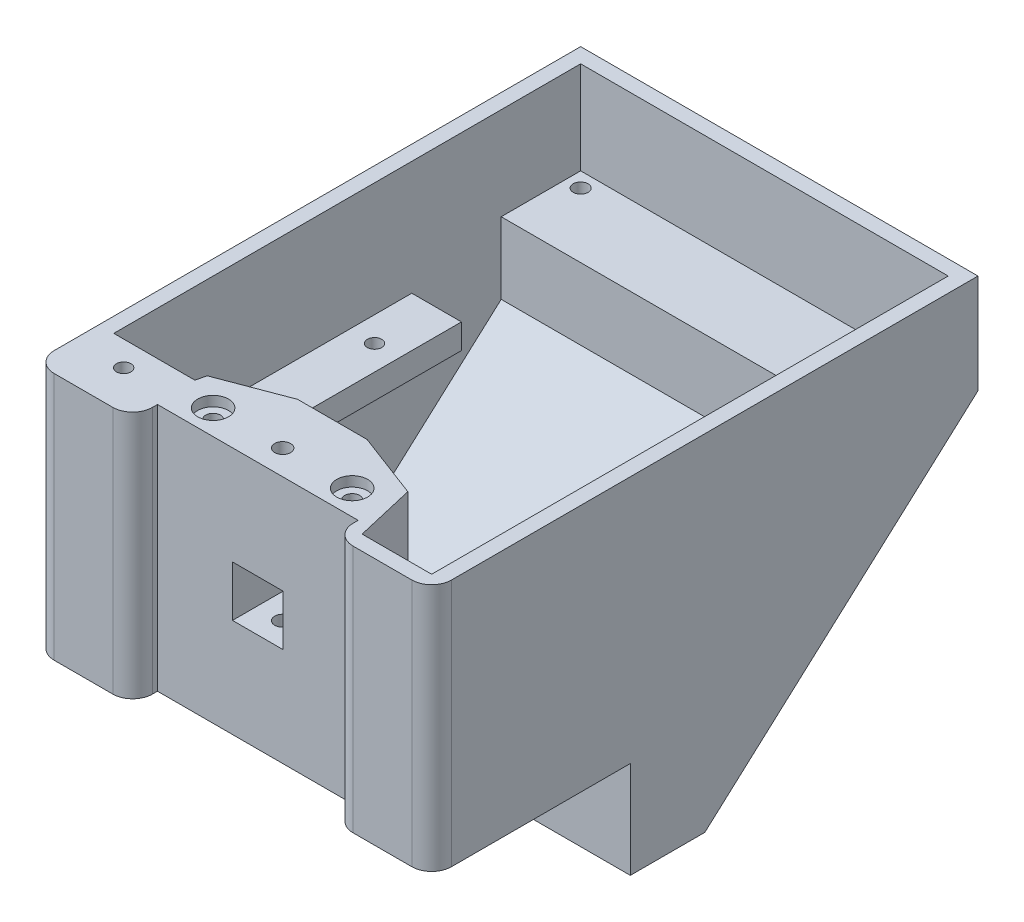
SolidWorks part; units mm, degrees
ref_plane "Спереди" through (0, 0, 0) normal (0, 0, 1) x (1, 0, 0)
ref_plane "Сверху" through (0, 0, 0) normal (0, 1, 0) x (1, 0, 0)
ref_plane "Справа" through (0, 0, 0) normal (1, 0, 0) x (0, 0, -1)
sketch "Sketch2" plane through (0, 0, 0) normal (1, 0, 0) x (0, 0, -1)
  line L0 (-27.3205, 20.9982) -> (-27.3205, -29.0018)
  line L1 (-27.3205, -29.0018) -> (12.6795, -29.0018)
  line L2 (12.6795, -29.0018) -> (12.6795, -48.5114)
  line L3 (12.6795, -48.5114) -> (27.6795, -48.5114)
  line L4 (82.6795, 20.9982) -> (82.6795, 0.9982)
  line L5 (82.6795, 20.9982) -> (-27.3205, 20.9982)
  line L6 (82.6795, 0.9982) -> (27.6795, -48.5114)
  dimension "D1" = 110
  dimension "D2" = 50
  dimension "D3" = 40
  dimension "D4" = 15
  dimension "D5" = 20
extrude "Boss-Extrude1" add sketch "Sketch2" along normal blind 80
shell "Shell1" thickness 3
sketch "Sketch3" plane through (0, 0, 24.3205) normal (0, 0, -1) x (-1, 0, 0)
  line L0 (-40, 20.9982) -> (-40, -26.0018) construction
  line L3 (-77, 20.9982) -> (-3, 20.9982) construction
  line L4 (-77, -26.0018) -> (-3, -26.0018) construction
  line L6 (-17, 20.9982) -> (-63, 20.9982)
  line L7 (-17, 20.9982) -> (-17, -26.0018)
  line L8 (-17, -26.0018) -> (-63, -26.0018)
  line L9 (-63, 20.9982) -> (-63, -26.0018)
  line L10 (-17, 20.9982) -> (-63, -26.0018) construction
  line L11 (-17, -26.0018) -> (-63, 20.9982) construction
  point P6 (-40, -2.5018)
  dimension "D1" = 46
extrude "Boss-Extrude2" add sketch "Sketch3" along normal blind 17
sketch "Sketch4" plane through (0, 0, 27.3205) normal (0, 0, 1) x (1, 0, 0)
  line L0 (0, 20.9982) -> (80, -29.0018) construction
  line L2 (45.1, -9.1018) -> (34.9, -9.1018)
  line L3 (45.1, -9.1018) -> (45.1, 1.0982)
  line L4 (45.1, 1.0982) -> (34.9, 1.0982)
  line L5 (34.9, -9.1018) -> (34.9, 1.0982)
  line L6 (45.1, -9.1018) -> (34.9, 1.0982) construction
  line L7 (45.1, 1.0982) -> (34.9, -9.1018) construction
  point P4 (40, -4.0018)
  dimension "D1" = 10.2
extrude "Cut-Extrude1" cut sketch "Sketch4" against normal up to surface (20 mm away) up to face at (40, -2.5018, 7.3205)
sketch "Sketch6" plane through (0, -29.0018, 0) normal (0, -1, 0) x (1, 0, 0)
  line L0 (40, 27.3205) -> (40, -12.6795) construction
  line L1 (47.5, -5.4795) -> (32.5, -5.4795)
  line L2 (47.5, -5.4795) -> (47.5, 7.3205)
  line L3 (47.5, 7.3205) -> (32.5, 7.3205)
  line L4 (32.5, -5.4795) -> (32.5, 7.3205)
  line L5 (47.5, -5.4795) -> (32.5, 7.3205) construction
  line L6 (47.5, 7.3205) -> (32.5, -5.4795) construction
  line L7 (80, -12.6795) -> (0, -12.6795) construction
  line L9 (80, 27.3205) -> (0, 27.3205) construction
  point P0 (40, 0.9205)
  dimension "D1" = 15
  dimension "D2" = 12.8
  dimension "D4" = 20
extrude "Cut-Extrude2" cut sketch "Sketch6" against normal up to surface (3 mm away) up to face at (40, -26.0018, 10.0705)
sketch "Sketch7" plane through (0, 0, 27.3205) normal (0, 0, 1) x (1, 0, 0)
  line L0 (40, 20.9982) -> (40, -29.0018) construction
  line L1 (80, 20.9982) -> (0, 20.9982) construction
  line L2 (80, -29.0018) -> (0, -29.0018) construction
  line L4 (60.2, -29.0018) -> (19.8, -29.0018)
  line L5 (60.2, -29.0018) -> (60.2, 20.9982)
  line L6 (60.2, 20.9982) -> (19.8, 20.9982)
  line L7 (19.8, -29.0018) -> (19.8, 20.9982)
  line L8 (60.2, -29.0018) -> (19.8, 20.9982) construction
  line L9 (60.2, 20.9982) -> (19.8, -29.0018) construction
  point P6 (40, -4.0018)
  dimension "D1" = 40.4
extrude "Cut-Extrude3" cut sketch "Sketch7" against normal blind 5
fillet "Fillet1" radius 4 4 edges at (19.8, -4.0018, 27.3205) (60.2, -4.0018, 27.3205) (80, -4.0018, 27.3205) (0, -4.0018, 27.3205)
sketch "Sketch12" plane through (0, 20.9982, 0) normal (0, 1, 0) x (1, 0, 0)
  line L0 (19.8, -22.3205) -> (19.8, -12.3205) construction
  line L1 (19.8, -12.3205) -> (60.2, -12.3205) construction
  line L2 (60.2, -12.3205) -> (60.2, -22.3205) construction
  line L3 (33, -7.3205) -> (19.8, -12.3205)
  line L4 (17, -7.3205) -> (63, -7.3205) construction
  line L5 (19.8, -12.3205) -> (17, -24.3205)
  line L6 (17, -24.3205) -> (17, -7.3205)
  line L7 (17, -7.3205) -> (33, -7.3205)
  line L8 (47, -7.3205) -> (63, -7.3205)
  line L9 (63, -7.3205) -> (63, -24.3205)
  line L10 (63, -24.3205) -> (60.2, -12.3205)
  line L11 (60.2, -12.3205) -> (47, -7.3205)
  dimension "D1" = 10
  dimension "D2" = 16
extrude "Cut-Extrude7" cut sketch "Sketch12" against normal up to surface (47 mm away) up to face at (40, -26.0018, 7.0205)
sketch "Sketch13" plane through (0, 20.9982, 0) normal (0, 1, 0) x (1, 0, 0)
  line L0 (19.8, -22.3205) -> (19.8, -12.3205) construction
  line L1 (19.8, -12.3205) -> (60.2, -12.3205) construction
  line L2 (60.2, -12.3205) -> (60.2, -22.3205) construction
  line L3 (60.2, -17.3205) -> (19.8, -17.3205) construction
  circle A0 centre (26, -17.3205) radius 1.5
  circle A1 centre (54, -17.3205) radius 1.5
  point P14 (40, -17.3205)
  dimension "D1" = 3
  dimension "D2" = 28
  dimension "D3" = 14
  dimension "D4" = 6.2
extrude "Cut-Extrude8" cut sketch "Sketch13" against normal blind 25
sketch "Sketch14" plane through (0, 20.9982, 0) normal (0, 1, 0) x (1, 0, 0)
  circle A0 centre (26, -17.3205) radius 3.1
  circle A1 centre (54, -17.3205) radius 3.1
  dimension "D1" = 6.2
extrude "Cut-Extrude9" cut sketch "Sketch14" against normal blind 2
sketch "Sketch17" plane through (77, 0, 0) normal (-1, 0, 0) x (0, 0, 1)
  line L0 (-45.6795, -2.0018) -> (-0.6795, -2.0018)
  line L1 (-0.6795, -2.0018) -> (-0.6795, -7.0018)
  line L2 (-0.6795, -7.0018) -> (-45.6795, -7.0018)
  line L3 (-45.6795, -7.0018) -> (-45.6795, -2.0018)
  line L4 (-79.6795, 20.9982) -> (24.3205, 20.9982) construction
  line L5 (-79.6795, 2.3342) -> (-79.6795, 20.9982) construction
  dimension "D1" = 45
  dimension "D2" = 5
  dimension "D3" = 23
  dimension "D4" = 34
extrude "Boss-Extrude5" add sketch "Sketch17" along normal up to surface (74 mm away) up to face at (3, -14.0994, -24.0865)
sketch "Sketch18" plane through (0, -2.0018, 0) normal (0, 1, 0) x (1, 0, 0)
  line L0 (40, 0.6795) -> (40, 45.6795) construction
  line L1 (3, 0.6795) -> (77, 0.6795) construction
  line L2 (3, 45.6795) -> (77, 45.6795) construction
  line L3 (77, 0.6795) -> (77, 45.6795) construction
  line L4 (13, 0.6795) -> (67, 0.6795)
  line L5 (13, 0.6795) -> (13, 45.6795)
  line L6 (13, 45.6795) -> (67, 45.6795)
  line L7 (67, 0.6795) -> (67, 45.6795)
  line L8 (13, 0.6795) -> (67, 45.6795) construction
  line L9 (13, 45.6795) -> (67, 0.6795) construction
  point P6 (40, 23.1795)
  dimension "D1" = 10
extrude "Cut-Extrude10" cut sketch "Sketch18" against normal up to next
sketch "Sketch19" plane through (0, -2.0018, 0) normal (0, 1, 0) x (1, 0, 0)
  line L0 (72, 45.6795) -> (72, 0.6795) construction
  line L1 (67, 45.6795) -> (77, 45.6795) construction
  line L2 (67, 0.6795) -> (77, 0.6795) construction
  line L3 (8, 45.6795) -> (8, 0.6795) construction
  line L4 (3, 45.6795) -> (13, 45.6795) construction
  line L5 (3, 0.6795) -> (13, 0.6795) construction
  circle A0 centre (72, 37.1795) radius 1.45
  circle A1 centre (72, 6.1795) radius 1.45
  circle A2 centre (8, 33.1795) radius 1.45
  circle A3 centre (8, 6.1795) radius 1.45
  point P20 (72, 23.1795)
  point P21 (8, 23.1795)
  dimension "D1" = 2.9
  dimension "D2" = 14
  dimension "D3" = 17
  dimension "D4" = 17
  dimension "D5" = 10
extrude "Cut-Extrude11" cut sketch "Sketch19" against normal up to next
sketch "Sketch21" plane through (0, -26.0018, 0) normal (0, 1, 0) x (1, 0, 0)
  line L0 (3, -24.3205) -> (3, -14.3205)
  line L1 (3, -24.3205) -> (3, 15.6795) construction
  line L2 (3, -14.3205) -> (19.3333, -14.3205)
  line L3 (19.8, -12.3205) -> (17, -24.3205) construction
  line L4 (19.3333, -14.3205) -> (17, -24.3205)
  line L6 (3, -24.3205) -> (17, -24.3205)
  dimension "D1" = 10
extrude "Boss-Extrude6" add sketch "Sketch21" along normal up to surface (47 mm away) up to face at (54, 20.9982, 20.4205)
sketch "Sketch22" plane through (0, 20.9982, 0) normal (0, 1, 0) x (1, 0, 0)
  line L0 (0, 82.6795) -> (0, -23.3205) construction
  line L1 (15.8, -27.3205) -> (4, -27.3205) construction
  circle A0 centre (10, -19.3205) radius 1.45
  dimension "D1" = 2.9
  dimension "D2" = 10
  dimension "D3" = 8
extrude "Cut-Extrude12" cut sketch "Sketch22" against normal through all
sketch "Sketch26" plane through (3, 0, 0) normal (1, 0, 0) x (0, 0, -1)
  line L0 (79.6795, 2.3342) -> (63.6795, 2.3342)
  line L1 (63.6795, 2.3342) -> (63.6795, -12.0686)
  line L2 (26.5281, -45.5114) -> (79.6795, 2.3342) construction
  line L3 (63.6795, -12.0686) -> (79.6795, 2.3342)
  dimension "D1" = 16
extrude "Boss-Extrude7" add sketch "Sketch26" along normal up to surface (74 mm away) up to face at (77, -14.0994, -24.0865)
sketch "Sketch27" plane through (0, 2.3342, 0) normal (0, 1, 0) x (1, 0, 0)
  line L0 (3, 76.6795) -> (77, 76.6795) construction
  line L1 (3, 79.6795) -> (3, 63.6795) construction
  line L2 (77, 79.6795) -> (77, 63.6795) construction
  line L3 (80, 82.6795) -> (0, 82.6795) construction
  circle A0 centre (6, 76.6795) radius 1.5
  circle A1 centre (74, 76.6795) radius 1.5
  point P10 (40, 76.6795)
  dimension "D1" = 3
  dimension "D2" = 68
  dimension "D3" = 34
  dimension "D4" = 6
extrude "Cut-Extrude14" cut sketch "Sketch27" against normal blind 10
sketch "Sketch28" plane through (0, 2.3342, 0) normal (0, 1, 0) x (1, 0, 0)
  line L1 (74, 79.9295) -> (71.1854, 78.3045)
  line L2 (71.1854, 78.3045) -> (71.1854, 75.0545)
  line L3 (71.1854, 75.0545) -> (74, 73.4295)
  line L4 (74, 73.4295) -> (76.8146, 75.0545)
  line L5 (76.8146, 75.0545) -> (76.8146, 78.3045)
  line L6 (76.8146, 78.3045) -> (74, 79.9295)
  line L7 (6, 73.4295) -> (8.8146, 75.0545)
  line L8 (8.8146, 75.0545) -> (8.8146, 78.3045)
  line L9 (8.8146, 78.3045) -> (6, 79.9295)
  line L10 (6, 79.9295) -> (3.1854, 78.3045)
  line L11 (3.1854, 78.3045) -> (3.1854, 75.0545)
  line L12 (3.1854, 75.0545) -> (6, 73.4295)
  circle A0 centre (74, 76.6795) radius 3.25 construction
  circle A1 centre (6, 76.6795) radius 3.25 construction
  dimension "D1" = 6.5
extrude "Cut-Extrude15" cut sketch "Sketch28" against normal blind 32 from offset 3 offset against normal yes
sketch "Sketch29" plane through (0, -29.0018, 0) normal (0, -1, 0) x (1, 0, 0)
  line L0 (0, 23.3205) -> (0, -12.6795) construction
  line L1 (7.1854, 17.6955) -> (10, 16.0705)
  line L2 (10, 16.0705) -> (12.8146, 17.6955)
  line L3 (12.8146, 17.6955) -> (12.8146, 20.9455)
  line L4 (12.8146, 20.9455) -> (10, 22.5705)
  line L5 (10, 22.5705) -> (7.1854, 20.9455)
  line L6 (7.1854, 20.9455) -> (7.1854, 17.6955)
  circle A0 centre (10, 19.3205) radius 3.25 construction
  dimension "D1" = 6.5
extrude "Cut-Extrude16" cut sketch "Sketch29" against normal blind 30
sketch "Sketch30" plane through (0, -26.0018, 0) normal (0, 1, 0) x (1, 0, 0)
  line L0 (77, -24.3205) -> (63, -24.3205)
  line L1 (63, -24.3205) -> (60.2, -12.3205)
  line L2 (63, -24.3205) -> (60.2, -12.3205) construction
  line L3 (60.2, -12.3205) -> (77, -12.3205)
  line L4 (77, -24.3205) -> (77, 15.6795) construction
  line L5 (77, -12.3205) -> (77, -24.3205)
  dimension "D1" = 12
extrude "Boss-Extrude8" add sketch "Sketch30" along normal blind 20
sketch "Sketch31" plane through (0, -6.0018, 0) normal (0, 1, 0) x (1, 0, 0)
  line L0 (76, -27.3205) -> (64.2, -27.3205) construction
  line L1 (80, -23.3205) -> (80, 12.6795) construction
  circle A0 centre (72, -21.3205) radius 1.5
  dimension "D3" = 3
  dimension "D1" = 6
  dimension "D2" = 8
extrude "Cut-Extrude17" cut sketch "Sketch31" against normal through all
sketch "Sketch32" plane through (0, -29.0018, 0) normal (0, -1, 0) x (1, 0, 0)
  line L1 (72, 24.5705) -> (69.1854, 22.9455)
  line L2 (69.1854, 22.9455) -> (69.1854, 19.6955)
  line L3 (69.1854, 19.6955) -> (72, 18.0705)
  line L4 (72, 18.0705) -> (74.8146, 19.6955)
  line L5 (74.8146, 19.6955) -> (74.8146, 22.9455)
  line L6 (74.8146, 22.9455) -> (72, 24.5705)
  circle A0 centre (72, 21.3205) radius 3.25 construction
  dimension "D1" = 6.5
extrude "Cut-Extrude18" cut sketch "Sketch32" against normal blind 15
sketch "Sketch33" plane through (0, -2.0018, 0) normal (0, 1, 0) x (1, 0, 0)
  line L0 (67, 40.6795) -> (77, 40.6795)
  line L1 (67, 0.6795) -> (67, 45.6795) construction
  line L2 (77, 0.6795) -> (77, 45.6795) construction
  line L3 (77, 40.6795) -> (77, 45.6795)
  line L4 (77, 45.6795) -> (67, 45.6795)
  line L5 (67, 45.6795) -> (67, 40.6795)
  dimension "D1" = 5
extrude "Cut-Extrude19" cut sketch "Sketch33" against normal up to next
sketch "Sketch34" plane through (0, 20.9982, 0) normal (0, 1, 0) x (1, 0, 0)
  line L0 (54, -17.3205) -> (26, -17.3205) construction
  circle A0 centre (40, -17.3205) radius 1.6
  dimension "D1" = 3.2
extrude "Cut-Extrude20" cut sketch "Sketch34" against normal through all
sketch "Sketch36" plane through (0, -29.0018, 0) normal (0, -1, 0) x (1, 0, 0)
  line L1 (38.375, 20.1351) -> (36.75, 17.3205)
  line L2 (36.75, 17.3205) -> (38.375, 14.5059)
  line L3 (38.375, 14.5059) -> (41.625, 14.5059)
  line L4 (41.625, 14.5059) -> (43.25, 17.3205)
  line L5 (43.25, 17.3205) -> (41.625, 20.1351)
  line L6 (41.625, 20.1351) -> (38.375, 20.1351)
  circle A0 centre (40, 17.3205) radius 3.25 construction
  dimension "D1" = 6.5
extrude "Cut-Extrude22" cut sketch "Sketch36" against normal blind 14
